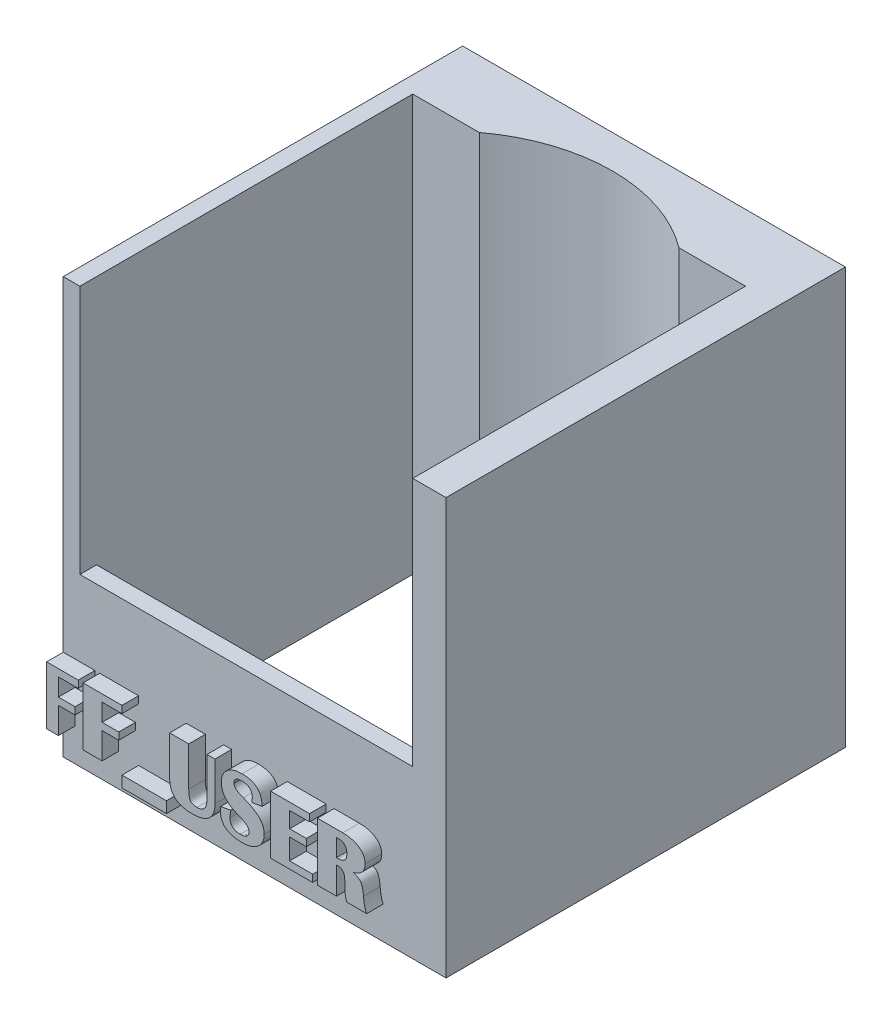
SolidWorks part; units mm, degrees
ref_plane "정면" through (0, 0, 0) normal (0, 0, 1) x (1, 0, 0)
ref_plane "윗면" through (0, 0, 0) normal (0, 1, 0) x (1, 0, 0)
ref_plane "우측면" through (0, 0, 0) normal (1, 0, 0) x (0, 0, -1)
sketch "Sketch1" plane through (0, 0, 0) normal (0, 1, 0) x (1, 0, 0)
  line L1 (0, 0) -> (670, 0)
  line L2 (0, 0) -> (0, 120)
  line L3 (0, 120) -> (670, 120)
  line L4 (670, 0) -> (670, 120)
  dimension "700" = 670
  dimension "D2" = 120
extrude "Boss-Extrude1" add sketch "Sketch1" along normal blind 530
sketch "Sketch2" plane through (0, 0, 0) normal (0, 0, 1) x (1, 0, 0)
  line L0 (0, 530) -> (0, 0) construction
  line L1 (10, 280) -> (110, 280)
  line L2 (10, 280) -> (10, 480)
  line L3 (10, 480) -> (110, 480)
  line L4 (110, 280) -> (110, 480)
  line L5 (0, 0) -> (670, 0) construction
  line L6 (120, 280) -> (120, 480)
  line L7 (120, 280) -> (220, 280)
  line L8 (220, 280) -> (220, 480)
  line L9 (120, 480) -> (220, 480)
  line L10 (230, 280) -> (230, 480)
  line L11 (230, 280) -> (330, 280)
  line L12 (330, 280) -> (330, 480)
  line L13 (230, 480) -> (330, 480)
  line L14 (340, 280) -> (340, 480)
  line L15 (340, 280) -> (440, 280)
  line L16 (440, 280) -> (440, 480)
  line L17 (340, 480) -> (440, 480)
  line L18 (450, 280) -> (450, 480)
  line L19 (450, 280) -> (550, 280)
  line L20 (550, 280) -> (550, 480)
  line L21 (450, 480) -> (550, 480)
  line L22 (560, 280) -> (560, 480)
  line L23 (560, 280) -> (660, 280)
  line L24 (660, 280) -> (660, 480)
  line L25 (560, 480) -> (660, 480)
  line L27 (10, 10) -> (660, 10)
  line L28 (10, 10) -> (10, 260)
  line L29 (10, 260) -> (660, 260)
  line L30 (660, 10) -> (660, 260)
  line L31 (0, 530) -> (670, 530) construction
  point P6 (10, 380)
  dimension "D1" = 100
  dimension "D2" = 200
  dimension "D3" = 10
  dimension "D4" = 50
  dimension "D6" = 10
  dimension "D7" = 20
  dimension "D5" = 6
extrude "Cut-Extrude1" cut sketch "Sketch2" against normal blind 100
sketch "Sketch3" plane through (0, 530, 0) normal (0, 1, 0) x (1, 0, 0)
  line L1 (670, 120) -> (0, 120) construction
  line L2 (0, 120) -> (0, 0) construction
  circle A0 centre (60, 60) radius 50
  circle A1 centre (170, 60) radius 50
  circle A2 centre (280, 60) radius 50
  circle A3 centre (390, 60) radius 50
  circle A4 centre (500, 60) radius 50
  circle A5 centre (610, 60) radius 50
  dimension "D1" = 100
  dimension "D2" = 10
  dimension "D3" = 10
  dimension "D4" = 6
extrude "Cut-Extrude2" cut sketch "Sketch3" against normal blind 260
hole_wizard "Ø12.0 (12) Diameter Hole2" positions "3DSketch1" profile "Sketch7" hole size "Ø12.0" standard "Ansi Metric"
sketch3d "3DSketch1"
  point P0 (59.7046, 270, -102.4117)
  point P2 (171.5567, 270, -102.6076)
  point P4 (280.8723, 270, -102.3969)
  point P6 (391.0687, 270, -102.7535)
  point P8 (500.7133, 270, -101.754)
  point P10 (609.5165, 270, -101.1227)
sketch "Sketch7" plane through (59.7046, 270, -102.4117) normal (1, 0, 0) x (0, 0, 1)
  line L0 (0, 0) -> (0, 33.6052)
  line L1 (0, 33.6052) -> (6, 30)
  line L2 (6, 30) -> (6, 0)
  line L5 (6, 0) -> (0, 0)
  line L10 (0, 33.6052) -> (-6, 30) construction
  line L11 (0, -6.35) -> (0, 107.95) construction
  dimension "구멍 지름" = 12
  dimension "구멍 깊이" = 30
  dimension "드릴 각도" = 118
sketch "Sketch8" plane through (0, 0, 0) normal (0, 0, 1) x (1, 0, 0)
  line L0 (660, 280) -> (660, 480) construction
  line L1 (10, 280) -> (660, 280)
  line L2 (10, 280) -> (10, 330)
  line L3 (10, 330) -> (660, 330)
  line L4 (660, 280) -> (660, 330)
  dimension "D1" = 50
extrude "Boss-Extrude2" add sketch "Sketch8" against normal blind 5
sketch "Sketch9" plane through (670, 0, 0) normal (1, 0, 0) x (0, 0, -1)
  line L0 (0, 530) -> (0, 0) construction
  line L1 (10, 10) -> (20, 10)
  line L2 (10, 10) -> (10, 260)
  line L3 (10, 260) -> (20, 260)
  line L4 (20, 10) -> (20, 260)
  line L5 (0, 0) -> (120, 0) construction
  dimension "D1" = 10
  dimension "D2" = 10
  dimension "D3" = 10
  dimension "D4" = 250
extrude "Cut-Extrude3" cut sketch "Sketch9" against normal blind 717
sketch "Sketch10" plane through (0, 10, 0) normal (0, 1, 0) x (1, 0, 0)
  line L0 (670, 120) -> (0, 120) construction
  line L1 (365, 61.9436) -> (350, 87.9243)
  line L2 (350, 87.9243) -> (320, 87.9243)
  line L3 (320, 87.9243) -> (305, 61.9436)
  line L4 (305, 61.9436) -> (320, 35.9628)
  line L5 (320, 35.9628) -> (350, 35.9628)
  line L6 (350, 35.9628) -> (365, 61.9436)
  line L7 (0, 120) -> (0, 0) construction
  circle A0 centre (335, 61.9436) radius 25.9808 construction
  dimension "D1" = 60
  dimension "D2" = 305
extrude "Cut-Extrude4" cut sketch "Sketch10" against normal blind 5
sketch "Sketch11" plane through (0, 0, -100) normal (0, 0, 1) x (1, 0, 0)
  line L0 (10, 10) -> (660, 10) construction
  line L1 (250, 10) -> (260, 10)
  line L2 (250, 10) -> (250, 110)
  line L3 (250, 110) -> (260, 110)
  line L4 (260, 10) -> (260, 110)
  line L5 (660, 10) -> (660, 260) construction
  line L6 (410, 10) -> (420, 10)
  line L7 (410, 10) -> (410, 110)
  line L8 (410, 110) -> (420, 110)
  line L9 (420, 10) -> (420, 110)
  line L10 (25, 198.4569) -> (325, 145.5588)
  line L11 (325, 145.5588) -> (325, 122.0178)
  line L12 (325, 122.0178) -> (345, 122.0178)
  line L13 (345, 122.0178) -> (345, 145.5588)
  line L14 (345, 145.5588) -> (645, 198.4569)
  line L15 (645, 198.4569) -> (25, 198.4569)
  point P18 (345, 133.7883)
  dimension "D1" = 10
  dimension "D2" = 10
  dimension "D3" = 100
  dimension "D4" = 100
  dimension "D5" = 150
  dimension "D6" = 240
  dimension "D7" = 20
  dimension "D8" = 65
  dimension "D9" = 100
  dimension "D10" = 620
  dimension "D11" = 100
extrude "Boss-Extrude3" add sketch "Sketch11" along normal blind 78 separate body
sketch "Sketch12" plane through (0, 0, -100) normal (0, 0, 1) x (1, 0, 0)
  line L0 (660, 260) -> (10, 260) construction
  line L1 (75.1986, 260) -> (95.1986, 260)
  line L2 (75.1986, 260) -> (75.1986, 230)
  line L3 (75.1986, 230) -> (95.1986, 230)
  line L4 (95.1986, 260) -> (95.1986, 230)
  line L5 (65.1986, 260) -> (65.1986, 240) construction
  line L6 (185.1986, 260) -> (185.1986, 230)
  line L7 (185.1986, 260) -> (205.1986, 260)
  line L8 (205.1986, 260) -> (205.1986, 230)
  line L9 (185.1986, 230) -> (205.1986, 230)
  line L10 (295.1986, 260) -> (295.1986, 230)
  line L11 (295.1986, 260) -> (315.1986, 260)
  line L12 (315.1986, 260) -> (315.1986, 230)
  line L13 (295.1986, 230) -> (315.1986, 230)
  line L14 (405.1986, 260) -> (405.1986, 230)
  line L15 (405.1986, 260) -> (425.1986, 260)
  line L16 (425.1986, 260) -> (425.1986, 230)
  line L17 (405.1986, 230) -> (425.1986, 230)
  line L18 (515.1986, 260) -> (515.1986, 230)
  line L19 (515.1986, 260) -> (535.1986, 260)
  line L20 (535.1986, 260) -> (535.1986, 230)
  line L21 (515.1986, 230) -> (535.1986, 230)
  line L22 (625.1986, 260) -> (625.1986, 230)
  line L23 (625.1986, 260) -> (645.1986, 260)
  line L24 (645.1986, 260) -> (645.1986, 230)
  line L25 (625.1986, 230) -> (645.1986, 230)
  dimension "D1" = 20
  dimension "D2" = 30
  dimension "D3" = 10
  dimension "D4" = 6
extrude "Cut-Extrude5" cut sketch "Sketch12" against normal blind 80
sketch "Sketch15" plane through (345, 0, 0) normal (1, 0, 0) x (0, 0, -1)
  line L0 (20, 10) -> (20, 260) construction
  line L1 (20, 121.4638) -> (50, 121.4638)
  line L2 (20, 121.4638) -> (20, 145)
  line L3 (20, 145) -> (50, 145)
  line L4 (50, 121.4638) -> (50, 145)
  line L5 (120, 530) -> (120, 0) construction
  line L6 (100, 116.0134) -> (70, 116.0134)
  line L7 (100, 116.0134) -> (100, 145)
  line L8 (100, 145) -> (70, 145)
  line L9 (70, 116.0134) -> (70, 145)
  line L10 (20, 260) -> (10, 260) construction
  dimension "D1" = 20
  dimension "D2" = 20
  dimension "D3" = 115
  dimension "D4" = 30
extrude "Cut-Extrude7" cut sketch "Sketch15" against normal blind 35
shell "Shell1" thickness 3
sketch "Sketch16" plane through (0, 122.0178, 0) normal (0, -1, 0) x (1, 0, 0)
  line L0 (345, -50) -> (325, -50) construction
  line L1 (328, -53) -> (342, -53)
  line L2 (328, -53) -> (328, -67)
  line L3 (328, -67) -> (342, -67)
  line L4 (342, -53) -> (342, -67)
  line L5 (325, -50) -> (325, -70) construction
  line L6 (345, -50) -> (345, -70) construction
  line L7 (325, -70) -> (345, -70) construction
  dimension "D1" = 3
  dimension "D2" = 3
  dimension "D3" = 3
  dimension "D4" = 3
extrude "Cut-Extrude8" cut sketch "Sketch16" against normal blind 35
sketch "Sketch17" plane through (0, 0, 0) normal (0, 0, 1) x (1, 0, 0)
  text T0 "<b>DIFF_USER</b>" font "Britannic Bold" height in points 72
extrude "Boss-Extrude4" add sketch "Sketch17" along normal blind 5
sketch "Sketch18" plane through (0, 0, 0) normal (0, 0, 1) x (1, 0, 0)
  line L0 (670, 530) -> (670, 0) construction
  line L1 (0, 0) -> (670, 0)
  line L2 (0, 0) -> (0, 280)
  line L3 (0, 280) -> (670, 280)
  line L4 (670, 0) -> (670, 280)
  dimension "D1" = 280
extrude "Cut-Extrude10" cut sketch "Sketch18" against normal blind 159
sketch "Sketch19" plane through (0, 0, 0) normal (0, 0, 1) x (1, 0, 0)
  line L0 (670, 280) -> (0, 280) construction
  line L1 (670, 280) -> (555, 280)
  line L2 (670, 280) -> (670, 530)
  line L3 (670, 530) -> (555, 530)
  line L4 (555, 280) -> (555, 530)
  line L5 (0, 530) -> (670, 530) construction
  line L6 (670, 530) -> (670, 280) construction
  line L8 (0, 530) -> (555, 530)
  line L9 (0, 530) -> (0, 280)
  line L10 (0, 280) -> (555, 280)
  line L11 (555, 530) -> (555, 280)
  dimension "D1" = 115
extrude "Cut-Extrude12" cut sketch "Sketch19" against normal blind 135 and the other way blind 59 contours L9 L10 L4 L8
sketch "Sketch20" plane through (0, 0, 0) normal (0, 0, 1) x (1, 0, 0)
  line L0 (670, 530) -> (670, 280) construction
  line L1 (555, 530) -> (670, 530)
  line L2 (555, 530) -> (555, 405)
  line L3 (555, 405) -> (670, 405)
  line L4 (670, 530) -> (670, 405)
  dimension "D1" = 125
extrude "Cut-Extrude13" cut sketch "Sketch20" against normal through all both and the other way through all
